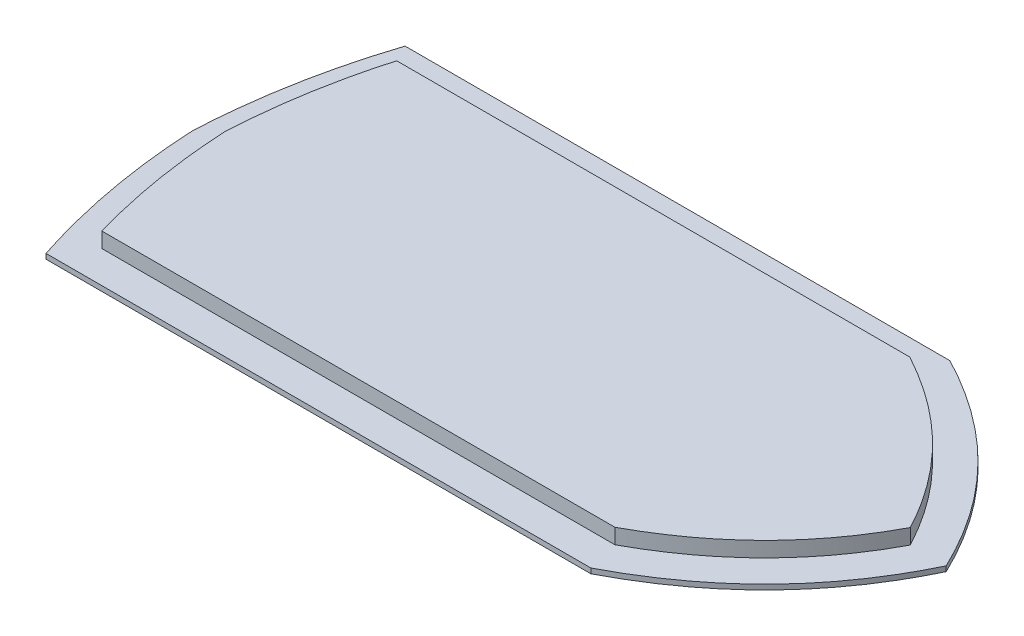
SolidWorks part; units mm, degrees
ref_plane "Alzado" through (0, 0, 0) normal (0, 0, 1) x (1, 0, 0)
ref_plane "Planta" through (0, 0, 0) normal (0, 1, 0) x (1, 0, 0)
ref_plane "Vista lateral" through (0, 0, 0) normal (1, 0, 0) x (0, 0, -1)
sketch "Croquis1" plane through (0, 0, 0) normal (0, 1, 0) x (1, 0, 0)
  line L4 (-68.8075, -35.7356) -> (38.8253, -35.7356)
  line L5 (38.8253, 35.2001) -> (-68.8075, 35.2001)
  line L6 (37.2477, 28.855) -> (-64.12, 28.855)
  line L7 (37.2477, -29.3905) -> (-64.12, -29.3905)
  spline S8 degree 3 poles (-75.3186, -0.2678) (-75.2307, -2.0744) (-75.1076, -3.8819) (-74.7687, -7.741) (-74.5413, -9.791) (-73.7212, -15.9126) (-72.991, -19.9487) (-71.1693, -27.9104) (-70.0803, -31.8385) (-68.8075, -35.7356) knots 0.290506 0.290506 0.290506 0.290506 0.392803 0.392803 0.510816 0.510816 0.746842 0.746842 0.980861 0.980861 0.980861 0.980861
  spline S9 degree 3 poles (38.8253, -35.7356) (38.8576, -35.7188) (38.8899, -35.702) (40.1635, -35.0391) (41.3631, -34.3795) (44.8796, -32.341) (47.1039, -30.9081) (53.4167, -26.4057) (57.1583, -23.1282) (63.8893, -15.9284) (66.8797, -12.0049) (70.872, -5.5027) (72.1215, -3.2285) (73.3802, -0.6522) (73.4731, -0.4603) (73.5654, -0.2678) knots 0.132683 0.132683 0.132683 0.132683 0.134252 0.134252 0.194615 0.194615 0.315342 0.315342 0.556794 0.556794 0.798247 0.798247 0.918973 0.918973 0.928653 0.928653 0.928653 0.928653
  spline S10 degree 3 poles (73.5654, -0.2678) (73.4731, -0.0752) (73.3802, 0.1167) (72.1215, 2.693) (70.872, 4.9672) (66.8797, 11.4694) (63.8893, 15.3929) (57.1583, 22.5927) (53.4167, 25.8702) (47.1039, 30.3726) (44.8796, 31.8055) (41.3631, 33.844) (40.1635, 34.5036) (38.8899, 35.1665) (38.8576, 35.1833) (38.8253, 35.2001) knots 0.132683 0.132683 0.132683 0.132683 0.142362 0.142362 0.263089 0.263089 0.504541 0.504541 0.745993 0.745993 0.86672 0.86672 0.927083 0.927083 0.928653 0.928653 0.928653 0.928653
  spline S11 degree 3 poles (-68.8075, 35.2001) (-70.0803, 31.303) (-71.1693, 27.3749) (-72.991, 19.4132) (-73.7212, 15.3771) (-74.5413, 9.2555) (-74.7687, 7.2055) (-75.1076, 3.3463) (-75.2307, 1.5389) (-75.3186, -0.2678) knots 0.290506 0.290506 0.290506 0.290506 0.524525 0.524525 0.760551 0.760551 0.878564 0.878564 0.980861 0.980861 0.980861 0.980861
  spline S12 degree 3 poles (-64.12, -29.3905) (-65.4858, -24.6464) (-66.5739, -19.8388) (-68.1908, -10.0988) (-68.7143, -5.198) (-68.9656, -0.2678) knots 0 0 0 0 0.5 0.5 1 1 1 1
  spline S13 degree 3 poles (-64.12, 28.855) (-65.4858, 24.1109) (-66.5739, 19.3033) (-68.1908, 9.5633) (-68.7143, 4.6625) (-68.9656, -0.2678) knots 0 0 0 0 0.5 0.5 1 1 1 1
  spline S14 degree 3 poles (66.4621, -0.2678) (64.8186, -3.3744) (62.9757, -6.3355) (59.8861, -10.5394) (58.8017, -11.901) (57.0916, -13.8822) (56.5077, -14.5325) (55.3119, -15.8127) (54.699, -16.4437) (51.5782, -19.5326) (48.9144, -21.7778) (43.2924, -25.8699) (40.3351, -27.7182) (37.2477, -29.3905) knots 0 0 0 0 0.25 0.25 0.375 0.375 0.4375 0.4375 0.5 0.5 0.75 0.75 1 1 1 1
  spline S15 degree 3 poles (66.4621, -0.2678) (64.8186, 2.8389) (62.9757, 5.8) (59.8861, 10.0039) (58.8017, 11.3655) (57.0916, 13.3467) (56.5077, 13.997) (55.3119, 15.2772) (54.699, 15.9082) (51.5782, 18.9971) (48.9144, 21.2423) (43.2924, 25.3344) (40.3351, 27.1827) (37.2477, 28.855) knots 0 0 0 0 0.25 0.25 0.375 0.375 0.4375 0.4375 0.5 0.5 0.75 0.75 1 1 1 1
extrude "Saliente-Extruir4" add sketch "Croquis1" along normal blind 1 contours L5 S11 S8 L4 S9 S10
sketch "Croquis4" plane through (0, 0, 0) normal (0, 1, 0) x (1, 0, 0)
  line L4 (-68.8075, -35.7356) -> (38.8253, -35.7356)
  line L5 (38.8253, 35.2001) -> (-68.8075, 35.2001)
  line L6 (37.2477, 28.855) -> (-64.12, 28.855)
  line L7 (37.2477, -29.3905) -> (-64.12, -29.3905)
  spline S8 degree 3 poles (-75.3186, -0.2678) (-75.2307, -2.0744) (-75.1076, -3.8819) (-74.7687, -7.741) (-74.5413, -9.791) (-73.7212, -15.9126) (-72.991, -19.9487) (-71.1693, -27.9104) (-70.0803, -31.8385) (-68.8075, -35.7356) knots 0.290506 0.290506 0.290506 0.290506 0.392803 0.392803 0.510816 0.510816 0.746842 0.746842 0.980861 0.980861 0.980861 0.980861
  spline S9 degree 3 poles (38.8253, -35.7356) (38.8576, -35.7188) (38.8899, -35.702) (40.1635, -35.0391) (41.3631, -34.3795) (44.8796, -32.341) (47.1039, -30.9081) (53.4167, -26.4057) (57.1583, -23.1282) (63.8893, -15.9284) (66.8797, -12.0049) (70.872, -5.5027) (72.1215, -3.2285) (73.3802, -0.6522) (73.4731, -0.4603) (73.5654, -0.2678) knots 0.132683 0.132683 0.132683 0.132683 0.134252 0.134252 0.194615 0.194615 0.315342 0.315342 0.556794 0.556794 0.798247 0.798247 0.918973 0.918973 0.928653 0.928653 0.928653 0.928653
  spline S10 degree 3 poles (73.5654, -0.2678) (73.4731, -0.0752) (73.3802, 0.1167) (72.1215, 2.693) (70.872, 4.9672) (66.8797, 11.4694) (63.8893, 15.3929) (57.1583, 22.5927) (53.4167, 25.8702) (47.1039, 30.3726) (44.8796, 31.8055) (41.3631, 33.844) (40.1635, 34.5036) (38.8899, 35.1665) (38.8576, 35.1833) (38.8253, 35.2001) knots 0.132683 0.132683 0.132683 0.132683 0.142362 0.142362 0.263089 0.263089 0.504541 0.504541 0.745993 0.745993 0.86672 0.86672 0.927083 0.927083 0.928653 0.928653 0.928653 0.928653
  spline S11 degree 3 poles (-68.8075, 35.2001) (-70.0803, 31.303) (-71.1693, 27.3749) (-72.991, 19.4132) (-73.7212, 15.3771) (-74.5413, 9.2555) (-74.7687, 7.2055) (-75.1076, 3.3463) (-75.2307, 1.5389) (-75.3186, -0.2678) knots 0.290506 0.290506 0.290506 0.290506 0.524525 0.524525 0.760551 0.760551 0.878564 0.878564 0.980861 0.980861 0.980861 0.980861
  spline S12 degree 3 poles (-64.12, -29.3905) (-65.4858, -24.6464) (-66.5739, -19.8388) (-68.1908, -10.0988) (-68.7143, -5.198) (-68.9656, -0.2678) knots 0 0 0 0 0.5 0.5 1 1 1 1
  spline S13 degree 3 poles (-64.12, 28.855) (-65.4858, 24.1109) (-66.5739, 19.3033) (-68.1908, 9.5633) (-68.7143, 4.6625) (-68.9656, -0.2678) knots 0 0 0 0 0.5 0.5 1 1 1 1
  spline S14 degree 3 poles (66.4621, -0.2678) (64.8186, -3.3744) (62.9757, -6.3355) (59.8861, -10.5394) (58.8017, -11.901) (57.0916, -13.8822) (56.5077, -14.5325) (55.3119, -15.8127) (54.699, -16.4437) (51.5782, -19.5326) (48.9144, -21.7778) (43.2924, -25.8699) (40.3351, -27.7182) (37.2477, -29.3905) knots 0 0 0 0 0.25 0.25 0.375 0.375 0.4375 0.4375 0.5 0.5 0.75 0.75 1 1 1 1
  spline S15 degree 3 poles (66.4621, -0.2678) (64.8186, 2.8389) (62.9757, 5.8) (59.8861, 10.0039) (58.8017, 11.3655) (57.0916, 13.3467) (56.5077, 13.997) (55.3119, 15.2772) (54.699, 15.9082) (51.5782, 18.9971) (48.9144, 21.2423) (43.2924, 25.3344) (40.3351, 27.1827) (37.2477, 28.855) knots 0 0 0 0 0.25 0.25 0.375 0.375 0.4375 0.4375 0.5 0.5 0.75 0.75 1 1 1 1
extrude "Saliente-Extruir5" add sketch "Croquis4" along normal blind 4 contours L7 S12 S13 L6 S15 S14
